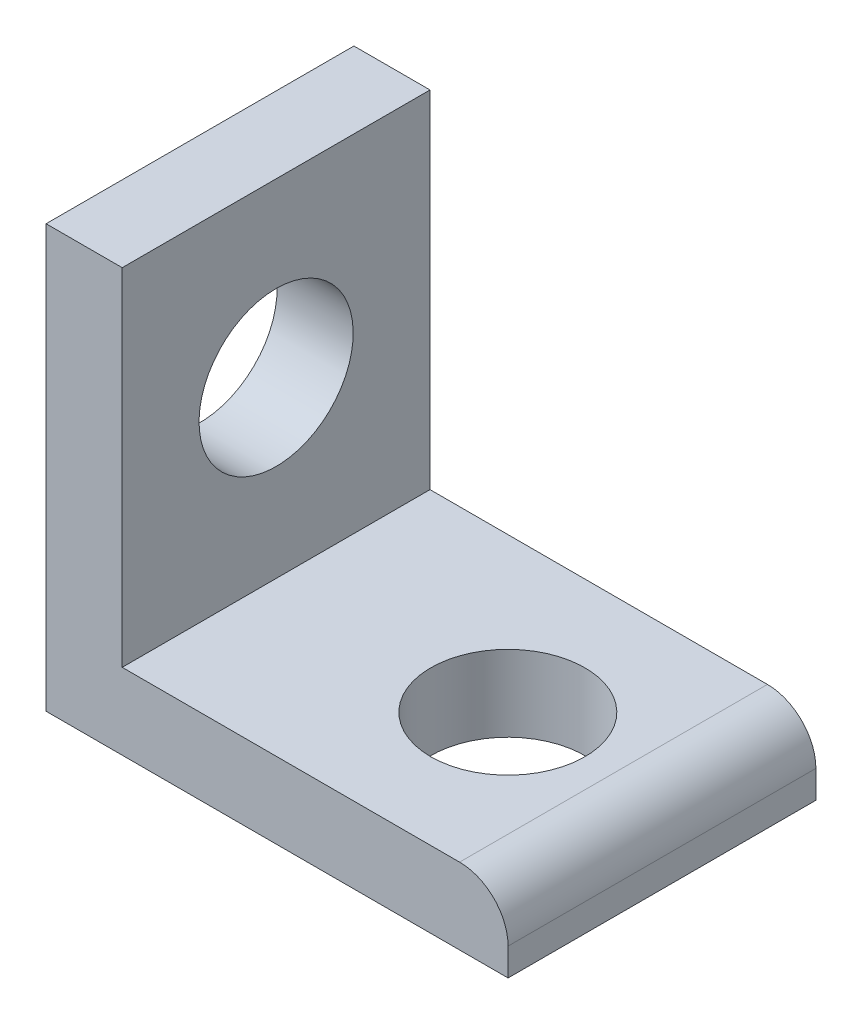
SolidWorks part; units mm, degrees
ref_plane "Front Plane" through (0, 0, 0) normal (0, 0, 1) x (1, 0, 0)
ref_plane "Top Plane" through (0, 0, 0) normal (0, 1, 0) x (1, 0, 0)
ref_plane "Right Plane" through (0, 0, 0) normal (1, 0, 0) x (0, 0, -1)
sketch "Sketch1" plane through (0, 0, 0) normal (0, 0, 1) x (1, 0, 0)
  line L0 (0, 8.71) -> (1.57, 8.71)
  line L1 (0, 0) -> (9.53, 0)
  line L2 (0, 0) -> (0, 8.71)
  line L3 (1.57, 8.71) -> (1.57, 1.57)
  line L4 (1.57, 1.57) -> (9.53, 1.57)
  line L5 (9.53, 1.57) -> (9.53, 0)
  dimension "D1" = 1.57
  dimension "D2" = 1.57
  dimension "D3" = 9.53
  dimension "D4" = 8.71
extrude "Boss-Extrude1" add sketch "Sketch1" along normal blind 6.35
sketch "Sketch2" plane through (0, 1.57, 0) normal (0, 1, 0) x (1, 0, 0)
  line L0 (9.53, -3.175) -> (-2.0199, -3.175) construction
  line L2 (9.53, -6.35) -> (9.53, 0) construction
  line L6 (0, -6.35) -> (0, 0) construction
  circle A0 centre (6.35, -3.175) radius 1.59
  point P2 (0, -3.175)
  dimension "D1" = 3.18
  dimension "D2" = 6.35
extrude "Cut-Extrude1" cut sketch "Sketch2" against normal up to surface (1.57 mm away) up to face at (4.765, 0, 3.175)
sketch "Sketch3" plane through (1.57, 0, 0) normal (1, 0, 0) x (0, 0, -1)
  line L0 (-3.175, 8.71) -> (-3.175, -0.5665) construction
  line L1 (-6.35, 8.71) -> (0, 8.71) construction
  line L2 (-6.35, 0) -> (0, 0) construction
  circle A0 centre (-3.175, 5.16) radius 1.59
  dimension "D1" = 3.18
  dimension "D2" = 5.16
extrude "Cut-Extrude2" cut sketch "Sketch3" against normal up to surface (1.57 mm away) up to face at (0, 4.355, 3.175)
fillet "Fillet1" radius 1 1 edges at (9.53, 1.57, 3.175)
